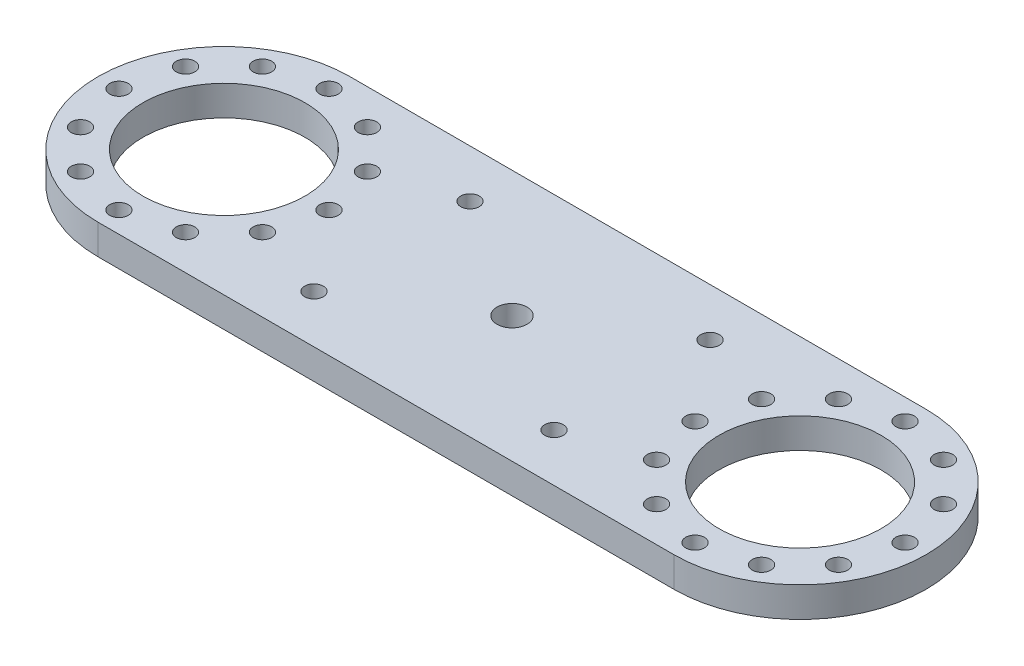
SolidWorks part; units mm, degrees
material "Thornel Mat VMA"
ref_plane "前视基准面" through (0, 0, 0) normal (0, 0, 1) x (1, 0, 0)
ref_plane "上视基准面" through (0, 0, 0) normal (0, 1, 0) x (1, 0, 0)
ref_plane "右视基准面" through (0, 0, 0) normal (1, 0, 0) x (0, 0, -1)
other "Configuration Table"
sketch "草图1" plane through (0, 0, 0) normal (0, 1, 0) x (1, 0, 0)
  line L0 (-48, 0) -> (48, 0) construction
  line L1 (-48, 21) -> (48, 21)
  line L2 (-48, -21) -> (48, -21)
  line L3 (0, -26.8061) -> (0, 32.763) construction
  arc A0 (-48, 21) -> (-48, -21) centre (-48, 0) ccw
  arc A1 (48, -21) -> (48, 21) centre (48, 0) ccw
  circle A2 centre (-48, 0) radius 13.5
  circle A3 centre (-48, 17.5) radius 1.55
  circle A4 centre (-20, 13) radius 1.55
  circle A5 centre (-20, -13) radius 1.55
  circle A6 centre (-39.25, 15.1554) radius 1.55
  circle A7 centre (-32.8446, 8.75) radius 1.55
  circle A8 centre (-30.5, 0) radius 1.55
  circle A9 centre (-32.8446, -8.75) radius 1.55
  circle A10 centre (-39.25, -15.1554) radius 1.55
  circle A11 centre (-48, -17.5) radius 1.55
  circle A12 centre (-56.75, -15.1554) radius 1.55
  circle A13 centre (-63.1554, -8.75) radius 1.55
  circle A14 centre (-65.5, 0) radius 1.55
  circle A15 centre (-63.1554, 8.75) radius 1.55
  circle A16 centre (-56.75, 15.1554) radius 1.55
  circle A17 centre (56.75, 15.1554) radius 1.55
  circle A18 centre (63.1554, 8.75) radius 1.55
  circle A19 centre (65.5, 0) radius 1.55
  circle A20 centre (63.1554, -8.75) radius 1.55
  circle A21 centre (56.75, -15.1554) radius 1.55
  circle A22 centre (48, -17.5) radius 1.55
  circle A23 centre (39.25, -15.1554) radius 1.55
  circle A24 centre (32.8446, -8.75) radius 1.55
  circle A25 centre (30.5, 0) radius 1.55
  circle A26 centre (39.25, 15.1554) radius 1.55
  circle A27 centre (20, -13) radius 1.55
  circle A28 centre (20, 13) radius 1.55
  circle A29 centre (48, 17.5) radius 1.55
  circle A30 centre (48, 0) radius 13.5
  circle A31 centre (32.8446, 8.75) radius 1.55
  point P2 (0, 0)
  point P40 (-48, 0)
  point P67 (48, 0)
  dimension "D2" = 21
  dimension "D3" = 27
  dimension "D5" = 3.1
  dimension "D9" = 3.1
  dimension "D1" = 96
  dimension "D4" = 17.5
  dimension "D6" = 26
  dimension "D7" = 20
  dimension "D8" = 13
  dimension "D10" = 12
extrude "凸台-拉伸1" add sketch "草图1" along normal blind 5
sketch "草图2" plane through (0, 5, 0) normal (0, 1, 0) x (1, 0, 0)
  circle A0 centre (0, 0) radius 2.5
  dimension "D1" = 5
extrude "切除-拉伸1" cut sketch "草图2" against normal blind 5
